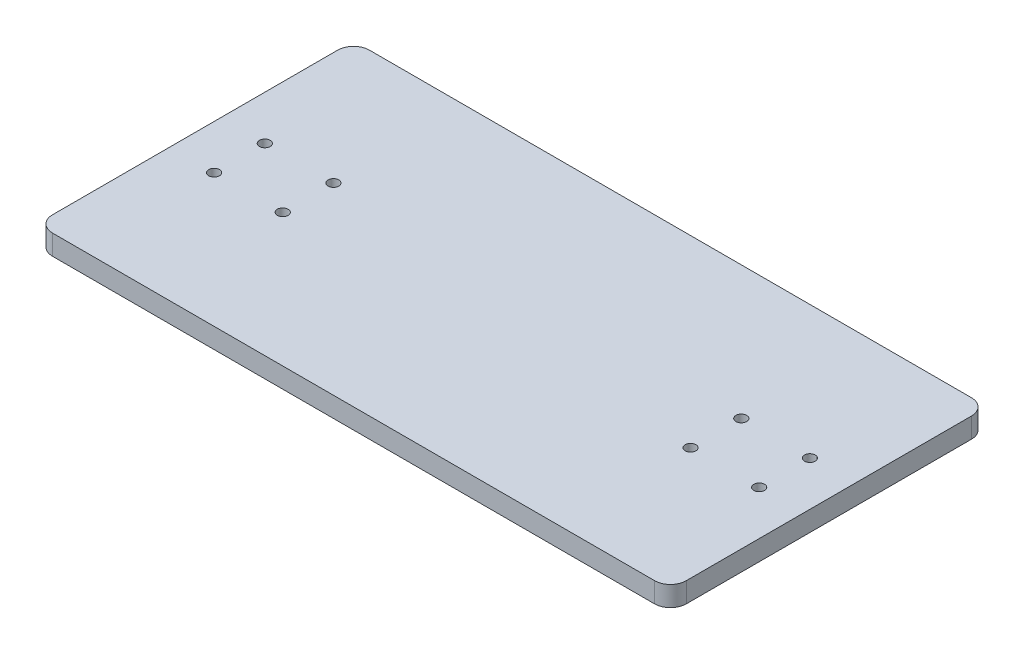
SolidWorks part; units mm, degrees
ref_plane "Front Plane" through (0, 0, 0) normal (0, 0, 1) x (1, 0, 0)
ref_plane "Top Plane" through (0, 0, 0) normal (0, 1, 0) x (1, 0, 0)
ref_plane "Right Plane" through (0, 0, 0) normal (1, 0, 0) x (0, 0, -1)
sketch "Sketch1" plane through (0, 0, 0) normal (0, 1, 0) x (1, 0, 0)
  line L0 (0, 50) -> (0, -50) construction
  line L1 (100, -50) -> (-100, -50)
  line L2 (100, -50) -> (100, 50)
  line L3 (100, 50) -> (-100, 50)
  line L4 (-100, -50) -> (-100, 50)
  line L5 (100, -50) -> (-100, 50) construction
  line L6 (100, 50) -> (-100, -50) construction
  line L7 (-100, 0) -> (100, 0) construction
  circle A0 centre (-86, 8) radius 1.7
  circle A1 centre (-86, -8) radius 1.7
  circle A2 centre (86, -8) radius 1.7
  circle A3 centre (86, 8) radius 1.7
  circle A4 centre (-64.35, 8) radius 1.7
  circle A5 centre (-64.35, -8) radius 1.7
  circle A6 centre (64.35, -8) radius 1.7
  circle A7 centre (64.35, 8) radius 1.7
  point P0 (0, 0)
  dimension "D3" = 3.4
  dimension "D5" = 8
  dimension "D6" = 3.4
  dimension "D7" = 64.35
  dimension "D1" = 200
  dimension "D2" = 100
  dimension "D4" = 14
extrude "Boss-Extrude1" add sketch "Sketch1" along normal blind 6.35
fillet "Fillet1" radius 5 4 edges at (-100, 3.175, -50) (100, 3.175, -50) (100, 3.175, 50) (-100, 3.175, 50)
